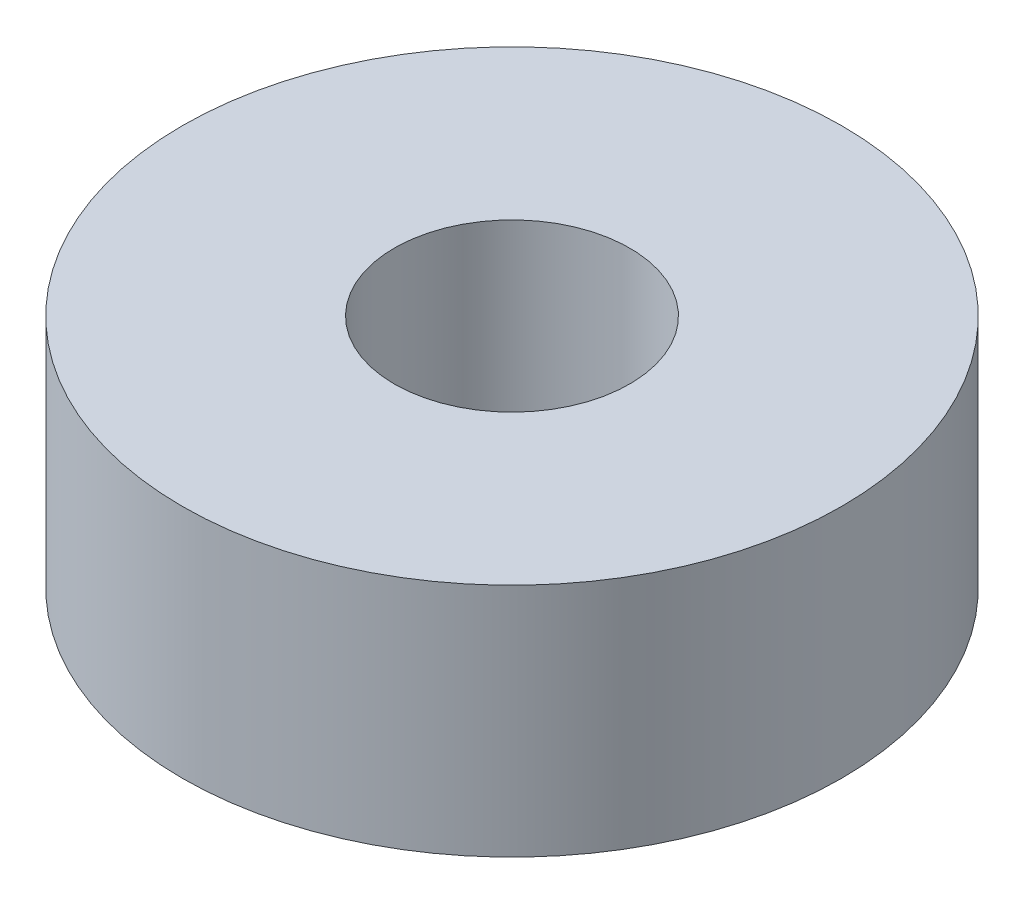
SolidWorks part; units mm, degrees
other "Markup1"
sketch "Sketch1" plane through (7, 5, 7) normal (0.293, 0.7294, 0.6181) x (0.8877, 0.0326, -0.4593)
material "合金钢"
ref_plane "前视基准面" through (0, 0, 0) normal (0, 0, 1) x (1, 0, 0)
ref_plane "上视基准面" through (0, 0, 0) normal (0, 1, 0) x (1, 0, 0)
ref_plane "右视基准面" through (0, 0, 0) normal (1, 0, 0) x (0, 0, -1)
sketch "草图1" plane through (0, 0, 0) normal (0, 1, 0) x (1, 0, 0)
  circle A0 centre (0, 0) radius 7
  circle A1 centre (0, 0) radius 2.5
  dimension "D1" = 5
  dimension "D2" = 14
extrude "凸台-拉伸1" add sketch "草图1" along normal blind 5
